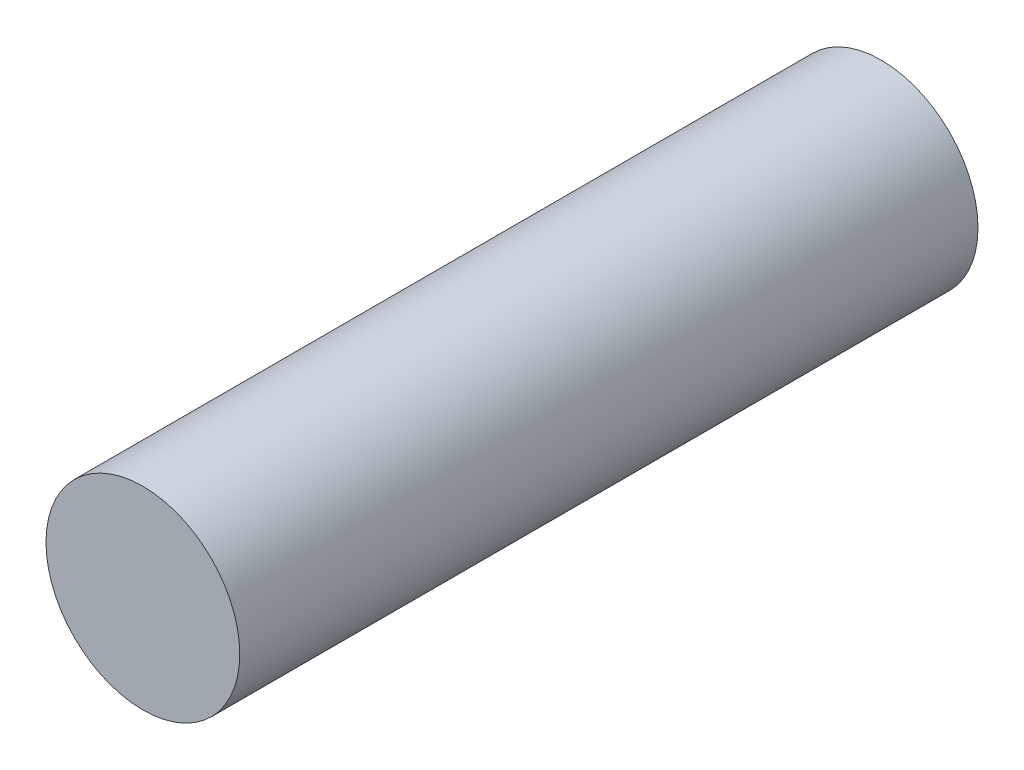
SolidWorks part; units mm, degrees
ref_plane "Front Plane" through (0, 0, 0) normal (0, 0, 1) x (1, 0, 0)
ref_plane "Top Plane" through (0, 0, 0) normal (0, 1, 0) x (1, 0, 0)
ref_plane "Right Plane" through (0, 0, 0) normal (1, 0, 0) x (0, 0, -1)
sketch "Sketch1" plane through (0, 0, 0) normal (0, 0, 1) x (1, 0, 0)
  circle A0 centre (0, 0) radius 5
extrude "Boss-Extrude1" add sketch "Sketch1" along normal blind 38.1
